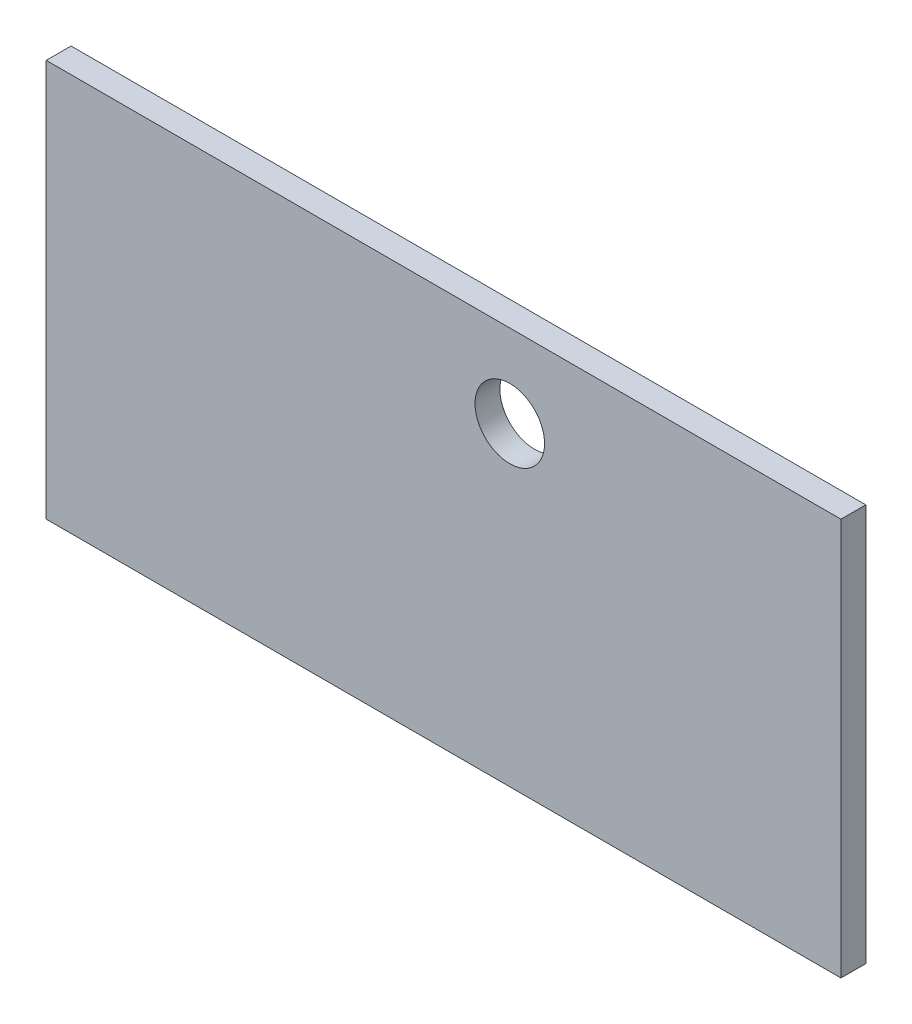
SolidWorks part; units mm, degrees
material "AISI 1015 Steel, Cold Drawn (SS)"
ref_plane "Front Plane" through (0, 0, 0) normal (0, 0, 1) x (1, 0, 0)
ref_plane "Top Plane" through (0, 0, 0) normal (0, 1, 0) x (1, 0, 0)
ref_plane "Right Plane" through (0, 0, 0) normal (1, 0, 0) x (0, 0, -1)
sketch "Sketch1" plane through (0, 0, 0) normal (0, 0, 1) x (1, 0, 0)
  line L1 (-152.4, -76.2) -> (152.4, -76.2)
  line L2 (-152.4, -76.2) -> (-152.4, 76.2)
  line L3 (-152.4, 76.2) -> (152.4, 76.2)
  line L4 (152.4, -76.2) -> (152.4, 76.2)
  line L5 (-152.4, -76.2) -> (152.4, 76.2) construction
  line L6 (-152.4, 76.2) -> (152.4, -76.2) construction
  point P0 (0, 0)
  dimension "D1" = 304.8
  dimension "D2" = 152.4
extrude "Boss-Extrude1" add sketch "Sketch1" along normal blind 9.525
sketch "Sketch2" plane through (0, 0, 9.525) normal (0, 0, 1) x (1, 0, 0)
  line L0 (133.35, -76.2) -> (133.35, -57.15) construction
  line L1 (-152.4, -76.2) -> (152.4, -76.2) construction
  line L2 (133.35, -57.15) -> (152.4, -57.15) construction
  line L3 (152.4, -76.2) -> (152.4, 76.2) construction
  line L4 (-152.4, -57.15) -> (-133.35, -57.15) construction
  line L5 (-152.4, 76.2) -> (-152.4, -76.2) construction
  line L6 (-133.35, -57.15) -> (133.35, -57.15) construction
  line L7 (133.35, -57.15) -> (133.35, -19.05) construction
  line L8 (133.35, -19.05) -> (-133.35, -19.05) construction
  line L9 (-133.35, -19.05) -> (-133.35, -57.15) construction
  line L10 (-133.35, -19.05) -> (0, -19.05) construction
  line L11 (0, -19.05) -> (133.35, -19.05) construction
  line L12 (-133.35, -38.1) -> (0, -38.1) construction
  line L13 (0, -38.1) -> (133.35, -38.1) construction
  line L14 (44.45, -19.05) -> (44.45, -57.15) construction
  line L15 (-44.45, -19.05) -> (-44.45, -57.15) construction
  line L16 (-88.9, -19.05) -> (-88.9, -57.15) construction
  line L17 (88.9, -19.05) -> (88.9, -57.15) construction
  line L18 (133.35, -44.174) -> (88.9, -44.174) construction
  line L19 (88.9, -44.174) -> (44.45, -44.174) construction
  line L20 (44.45, -44.174) -> (0, -44.174) construction
  line L21 (0, -44.174) -> (-44.45, -44.174) construction
  line L22 (-44.45, -44.174) -> (-88.9, -44.174) construction
  line L23 (-88.9, -44.174) -> (-133.35, -44.174) construction
  line L24 (0, -57.15) -> (0, -44.174) construction
  line L25 (0, -44.174) -> (0, -19.05) construction
  circle A0 centre (133.35, -57.15) radius 6.985
  circle A1 centre (0, -57.15) radius 6.985
  circle A2 centre (-133.35, -57.15) radius 6.985
  circle A3 centre (-133.35, -19.05) radius 6.985
  circle A4 centre (0, -19.05) radius 6.985
  circle A5 centre (133.35, -19.05) radius 6.985
  circle A6 centre (44.45, -19.05) radius 6.985
  circle A7 centre (-44.45, -19.05) radius 6.985
  circle A8 centre (-44.45, -57.15) radius 6.985
  circle A9 centre (44.45, -57.15) radius 6.985
  circle A10 centre (-88.9, -19.05) radius 6.985
  circle A11 centre (-88.9, -57.15) radius 6.985
  circle A12 centre (88.9, -19.05) radius 6.985
  circle A13 centre (88.9, -57.15) radius 6.985
  dimension "D3" = 13.97
  dimension "D1" = 19.05
  dimension "D2" = 19.05
  dimension "D4" = 38.1
extrude "Cut-Extrude1" [suppressed] cut sketch "Sketch2" against normal up to surface (6.35 mm away) contours A4 | A12 | A0 | A9 | A8 | A10 | A2
sketch "Sketch3" [suppressed] plane through (0, 0, 12.7) normal (0, 0, 1) x (1, 0, 0)
  line L0 (-95.25, 38.1) -> (-44.45, 38.1) construction
  line L1 (-95.25, 63.5) -> (-95.25, -63.5) construction
  line L2 (-44.45, 38.1) -> (-25.4, 38.1) construction
  line L3 (-25.4, 38.1) -> (76.2, 38.1) construction
  line L4 (76.2, 38.1) -> (95.25, 38.1) construction
  line L5 (95.25, -63.5) -> (95.25, 63.5) construction
  line L6 (95.25, 63.5) -> (-95.25, 63.5) construction
  line L7 (-44.45, -38.1) -> (95.25, -38.1) construction
  line L8 (60.1845, -38.1) -> (60.1845, -63.5) construction
  line L9 (-95.25, -63.5) -> (95.25, -63.5) construction
  line L10 (28.5063, 38.1) -> (28.5063, 63.5) construction
  line L11 (-44.45, -38.1) -> (-44.45, 38.1) construction
  line L12 (76.2, 38.1) -> (76.2, -38.1) construction
  line L13 (76.2, 0) -> (-25.4, 0) construction
  circle A0 centre (-25.4, 38.1) radius 6.985
  circle A1 centre (76.2, 38.1) radius 6.985
  circle A2 centre (-25.4, -38.1) radius 6.985
  circle A3 centre (76.2, -38.1) radius 6.985
  circle A4 centre (76.2, 0) radius 6.985
  circle A5 centre (-25.4, 0) radius 6.985
  circle A6 centre (25.4, 38.1) radius 6.985
  circle A7 centre (25.4, -38.1) radius 6.985
  dimension "D4" = 13.97
  dimension "D1" = 50.8
  dimension "D2" = 19.05
  dimension "D3" = 50.8
  dimension "D5" = 25.4
  dimension "D6" = 50.8
extrude "Cut-Extrude2" [suppressed] cut sketch "Sketch3" against normal up to surface (25.4 mm away) contours A0 | A1 | A3 | A2 | A6 | A7
sketch "Sketch5" plane through (0, 0, 0) normal (0, 0, -1) x (-1, 0, 0)
  line L0 (-152.4, 44.45) -> (-25.4, 44.45) construction
  line L1 (-152.4, -76.2) -> (-152.4, 76.2) construction
  line L2 (-25.4, 44.45) -> (-25.4, 76.2) construction
  line L3 (-152.4, 76.2) -> (152.4, 76.2) construction
  circle A0 centre (-25.4, 44.45) radius 13.335
  dimension "D3" = 26.67
  dimension "D1" = 127
  dimension "D2" = 31.75
extrude "Cut-Extrude3" cut sketch "Sketch5" against normal through all contours A0
hole_wizard "1 (1.05) Diameter Hole1" positions "Sketch6" profile "Sketch7" hole size "1" standard "ANSI Inch"
sketch "Sketch6" plane through (1137.1329, -76.2, 69.85) normal (0, 0, 1) x (1, 0, 0)
  point P0 (-1111.7329, 120.65)
sketch "Sketch7" plane through (25.4, 44.45, 69.85) normal (1, 0, 0) x (0, -1, 0)
  line L0 (0, 0) -> (0, 68.3365)
  line L1 (0, 68.3365) -> (13.335, 60.324)
  line L2 (13.335, 60.324) -> (13.335, 0)
  line L3 (13.335, 0) -> (0, 0)
  line L4 (0, 68.3365) -> (-13.335, 60.324) construction
  line L5 (0, -6.35) -> (0, 107.95) construction
  dimension "Hole Dia." = 26.67
  dimension "Hole Depth" = 60.324
  dimension "Drill Angle" = 118
hole_wizard "1 (1.05) Diameter Hole2" positions "Sketch8" profile "Sketch9" hole size "1" standard "ANSI Inch"
sketch "Sketch8" plane through (1137.1329, -76.2, 9.525) normal (0, 0, 1) x (1, 0, 0)
  point P0 (-1111.7329, 120.65)
sketch "Sketch9" plane through (25.4, 44.45, 9.525) normal (1, 0, 0) x (0, -1, 0)
  line L0 (0, 0) -> (0, 68.3365)
  line L1 (0, 68.3365) -> (13.335, 60.324)
  line L2 (13.335, 60.324) -> (13.335, 0)
  line L3 (13.335, 0) -> (0, 0)
  line L4 (0, 68.3365) -> (-13.335, 60.324) construction
  line L5 (0, -6.35) -> (0, 107.95) construction
  dimension "Hole Dia." = 26.67
  dimension "Hole Depth" = 60.324
  dimension "Drill Angle" = 118
